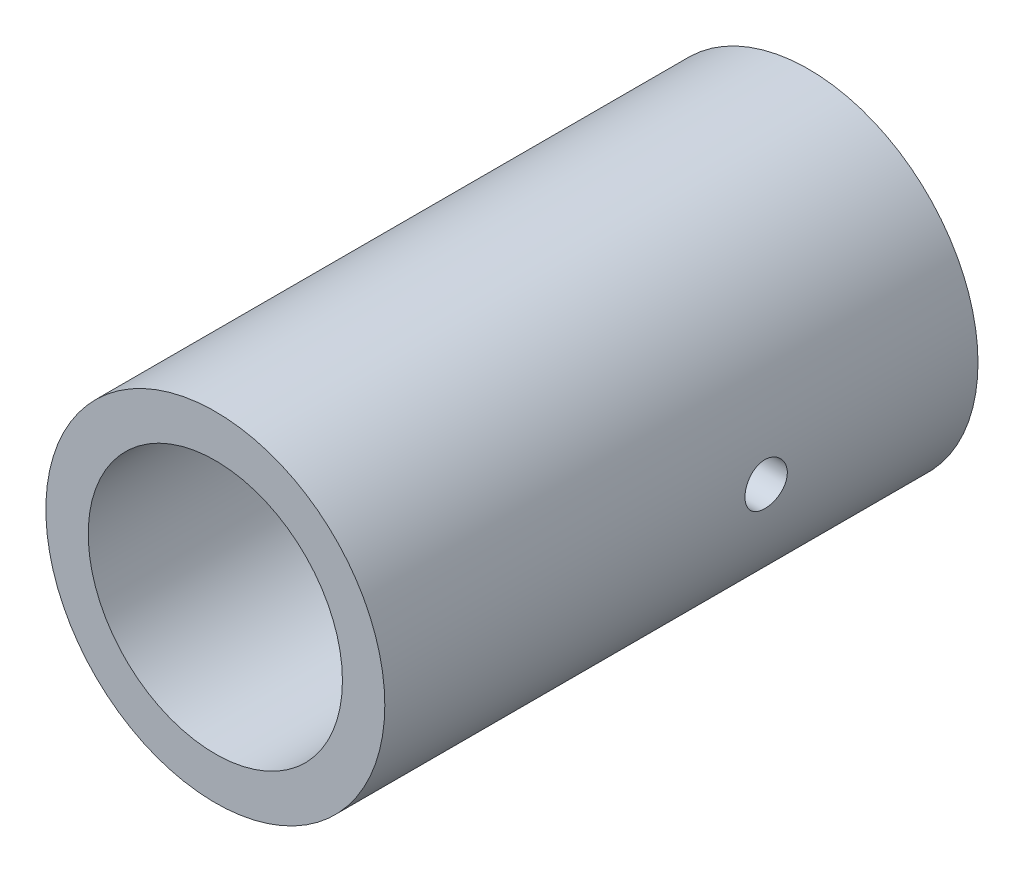
SolidWorks part; units mm, degrees
ref_plane "Front Plane" through (0, 0, 0) normal (0, 0, 1) x (1, 0, 0)
ref_plane "Top Plane" through (0, 0, 0) normal (0, 1, 0) x (1, 0, 0)
ref_plane "Right Plane" through (0, 0, 0) normal (1, 0, 0) x (0, 0, -1)
sketch "Sketch1" plane through (0, 0, 0) normal (0, 0, 1) x (1, 0, 0)
  circle A0 centre (0, 0) radius 20
  dimension "D1" = 40
extrude "Boss-Extrude1" add sketch "Sketch1" along normal blind 70 contours A0
sketch "Sketch2" plane through (0, 0, 70) normal (0, 0, 1) x (1, 0, 0)
  circle A0 centre (0, 0) radius 15
  dimension "D1" = 30
extrude "Cut-Extrude1" cut sketch "Sketch2" against normal blind 70
ref_plane "Plane1" through (20, 0, 0) normal (1, 0, 0) x (0, 0, -1)
sketch "Sketch3" plane through (20, 0, 0) normal (1, 0, 0) x (0, 0, -1)
  circle A0 centre (-25, 0) radius 2.5
  dimension "D2" = 5
extrude "Cut-Extrude2" cut sketch "Sketch3" against normal blind 53
